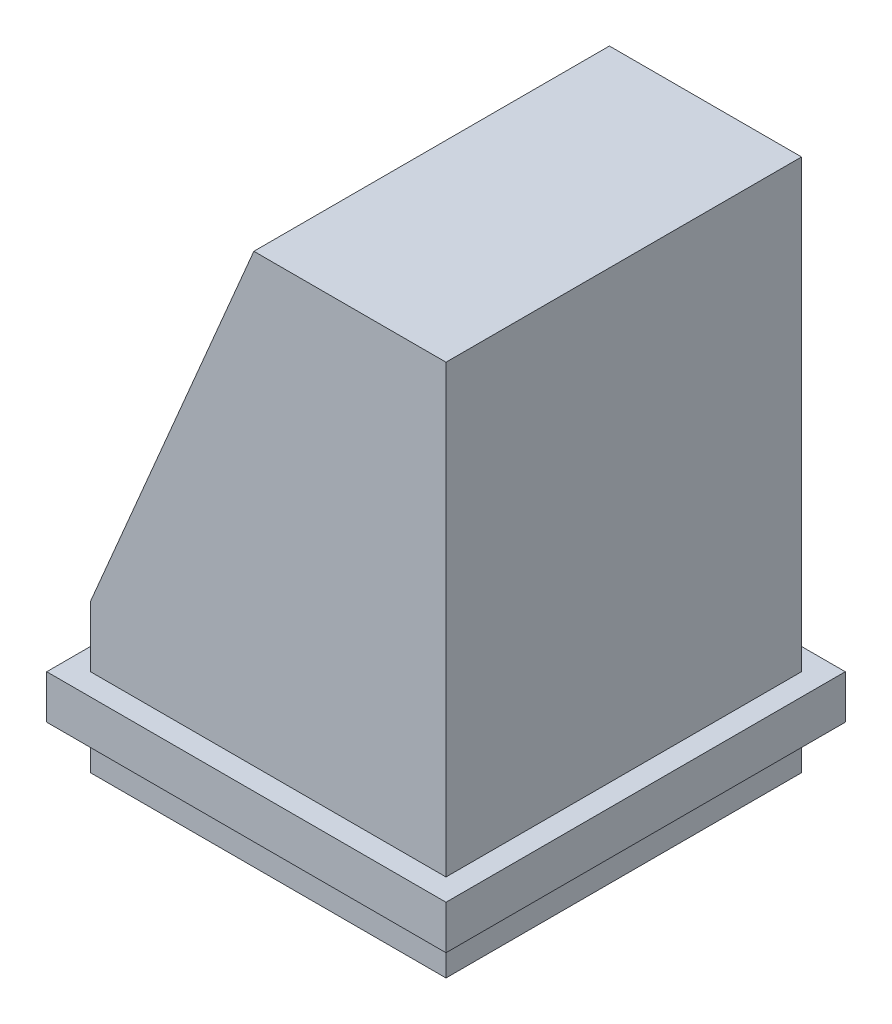
SolidWorks part; units mm, degrees
ref_plane "Front Plane" through (0, 0, 0) normal (0, 0, 1) x (1, 0, 0)
ref_plane "Top Plane" through (0, 0, 0) normal (0, 1, 0) x (1, 0, 0)
ref_plane "Right Plane" through (0, 0, 0) normal (1, 0, 0) x (0, 0, -1)
sketch "Sketch2" plane through (0, 0, 0) normal (0, 1, 0) x (1, 0, 0)
  line L1 (0, 0) -> (812.8, 0)
  line L2 (0, 0) -> (0, 812.8)
  line L3 (0, 812.8) -> (812.8, 812.8)
  line L4 (812.8, 0) -> (812.8, 812.8)
  dimension "D1" = 812.8
  dimension "D2" = 812.8
extrude "Boss-Extrude1" add sketch "Sketch2" along normal blind 1219.2
ref_plane "Plane1" through (0, 100, 0) normal (0, 1, 0) x (1, 0, 0)
sketch "Sketch3" plane through (0, 100, 0) normal (0, 1, 0) x (1, 0, 0)
  line L1 (-50, -50) -> (862.8, -50)
  line L2 (-50, -50) -> (-50, 862.8)
  line L3 (-50, 862.8) -> (862.8, 862.8)
  line L4 (862.8, -50) -> (862.8, 862.8)
  line L6 (0, 0) -> (812.8, 0)
  line L7 (0, 0) -> (0, 812.8)
  line L8 (0, 812.8) -> (812.8, 812.8)
  line L9 (812.8, 0) -> (812.8, 812.8)
  point P11 (857.8797, 879.0425)
  dimension "D1" = 812.8
  dimension "D2" = 812.8
  dimension "D3" = 50
  dimension "D4" = 50
  dimension "D5" = 50
  dimension "D6" = 50
extrude "Boss-Extrude2" add sketch "Sketch3" along normal blind 100
chamfer "Chamfer4" distance 880 angle 23 1 edges at (0, 1219.2, -406.4)
